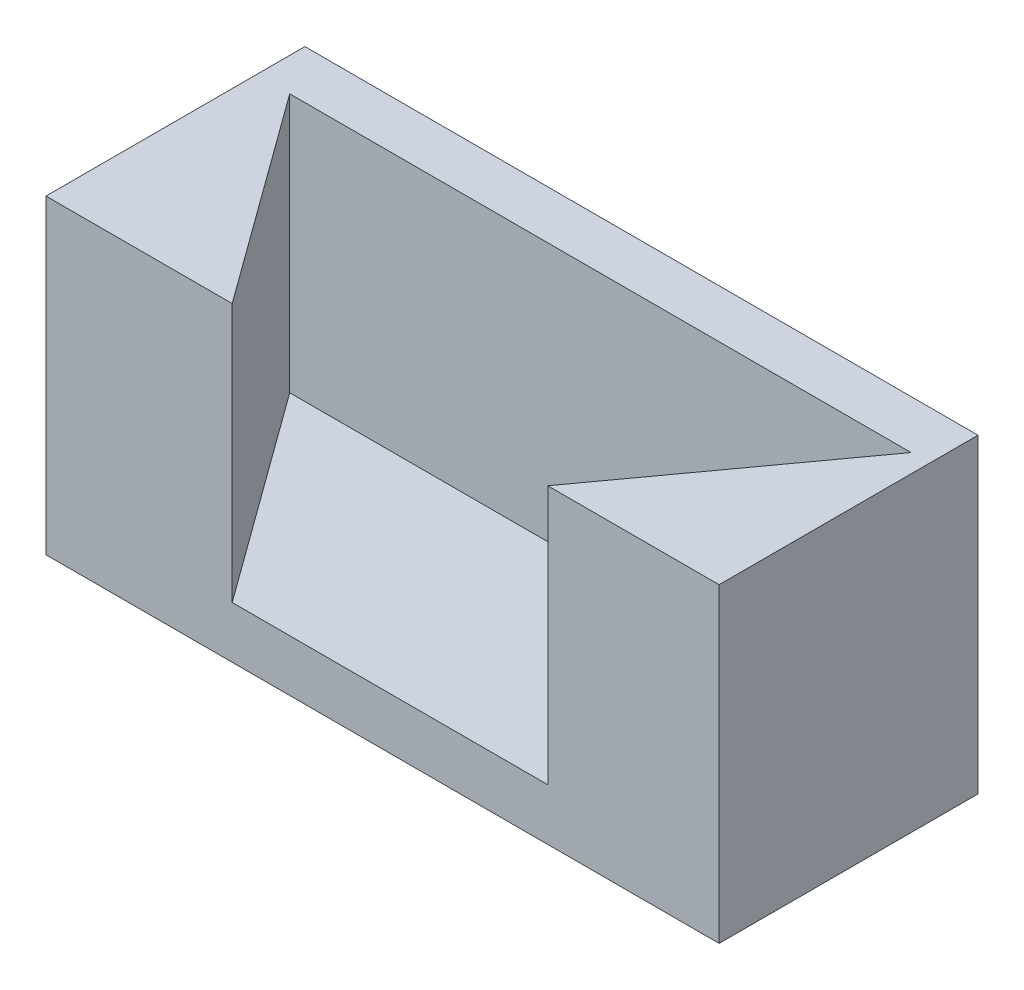
SolidWorks part; units mm, degrees
ref_plane "Front Plane" through (0, 0, 0) normal (0, 0, 1) x (1, 0, 0)
ref_plane "Top Plane" through (0, 0, 0) normal (0, 1, 0) x (1, 0, 0)
ref_plane "Right Plane" through (0, 0, 0) normal (1, 0, 0) x (0, 0, -1)
sketch "Sketch3" plane through (0, 0, 0) normal (0, 1, 0) x (1, 0, 0)
  line L1 (-6.5, -2.5) -> (6.5, -2.5)
  line L2 (-6.5, -2.5) -> (-6.5, 2.5)
  line L3 (-6.5, 2.5) -> (6.5, 2.5)
  line L4 (6.5, -2.5) -> (6.5, 2.5)
  line L5 (-6.5, -2.5) -> (6.5, 2.5) construction
  line L6 (-6.5, 2.5) -> (6.5, -2.5) construction
  point P0 (0, 0)
  dimension "D1" = 13
  dimension "D2" = 5
extrude "Boss-Extrude2" add sketch "Sketch3" along normal blind 6
sketch "Sketch5" plane through (0, 6, 0) normal (0, 1, 0) x (1, 0, 0)
  line L0 (-2.9042, -2.5) -> (-5.8566, 1.5636)
  line L1 (-6.5, -2.5) -> (6.5, -2.5) construction
  line L2 (-5.8566, 1.5636) -> (6.1434, 1.5636)
  line L3 (6.1434, 1.5636) -> (3.1911, -2.5)
  line L4 (-2.9042, -2.5) -> (3.1911, -2.5)
  dimension "D1" = 12
  dimension "D2" = 6.0952
  dimension "D3" = 126
  dimension "D4" = 126
extrude "Cut-Extrude2" cut sketch "Sketch5" against normal blind 5
